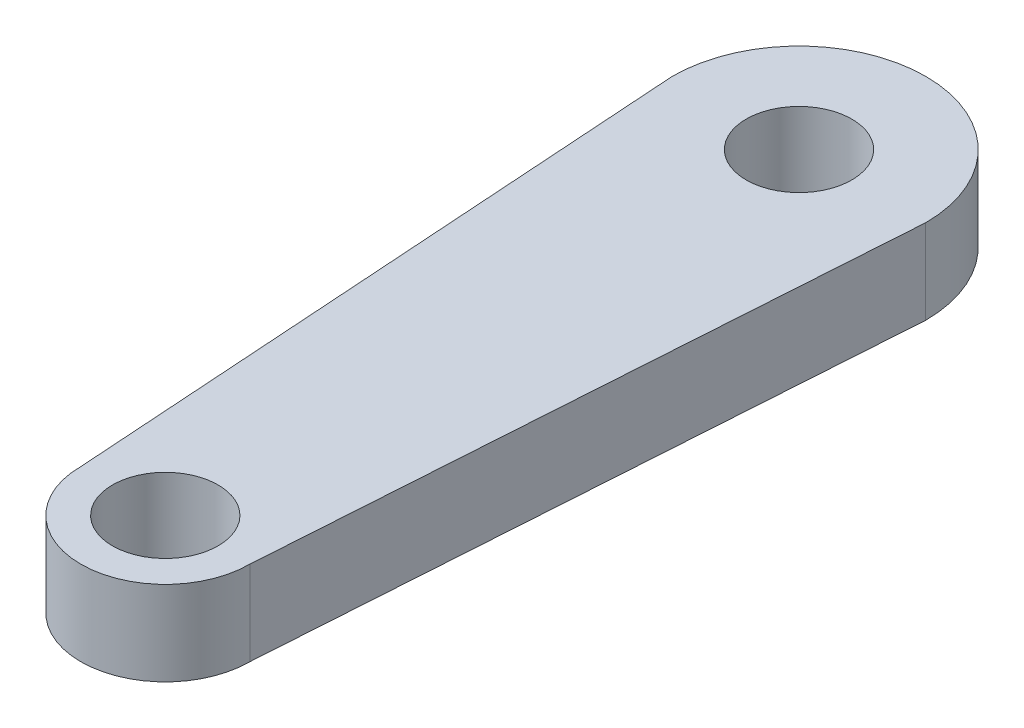
SolidWorks part; units mm, degrees
ref_plane "Front Plane" through (0, 0, 0) normal (0, 0, 1) x (1, 0, 0)
ref_plane "Top Plane" through (0, 0, 0) normal (0, 1, 0) x (1, 0, 0)
ref_plane "Right Plane" through (0, 0, 0) normal (1, 0, 0) x (0, 0, -1)
sketch "Sketch1" plane through (0, 0, 0) normal (0, 1, 0) x (1, 0, 0)
  line L0 (-3, 5) -> (-2, -10)
  line L5 (3, 5) -> (2, -10)
  arc A0 (2.9735, 4.6018) -> (-2.9735, 4.6018) centre (0, 5) ccw
  arc A1 (-2, -10) -> (2, -10) centre (0, -10) ccw
  circle A2 centre (0, 5) radius 1.25
  circle A3 centre (0, -10) radius 1.25
  point P0 (0, 0)
  dimension "D3" = 4
  dimension "D1" = 6
  dimension "D2" = 2.5
  dimension "D4" = 2.5
  dimension "D5" = 15
extrude "Boss-Extrude1" add sketch "Sketch1" along normal mid plane 2 contours L0 A1 L5 A0 A3 A2
